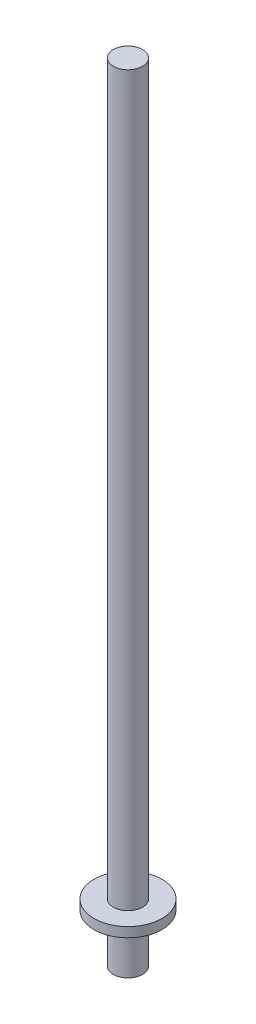
SolidWorks part; units mm, degrees
ref_plane "Front Plane" through (0, 0, 0) normal (0, 0, 1) x (1, 0, 0)
ref_plane "Top Plane" through (0, 0, 0) normal (0, 1, 0) x (1, 0, 0)
ref_plane "Right Plane" through (0, 0, 0) normal (1, 0, 0) x (0, 0, -1)
sketch "Sketch1" plane through (0, 0, 0) normal (0, 0, 1) x (1, 0, 0)
  line L0 (0, 0) -> (3, 0)
  line L1 (9.9, 0) -> (-9.9, 0) construction
  line L2 (3, 0) -> (3, -150)
  line L3 (3, -150) -> (7, -150)
  line L4 (7, -150) -> (7, -152)
  line L5 (7, -152) -> (3, -152)
  line L6 (3, -152) -> (3, -162)
  line L7 (3, -162) -> (0, -162)
  line L8 (0, -162) -> (0, 0)
  line L9 (0, 11.6744) -> (0, -76.3737) construction
  line L10 (0, -9.9) -> (0, 9.9) construction
  dimension "D1" = 3
  dimension "D2" = 150
  dimension "D3" = 2
  dimension "D4" = 10
  dimension "D5" = 3
  dimension "D6" = 4
revolve "Revolve1" add sketch "Sketch1" angle 360 about L9
